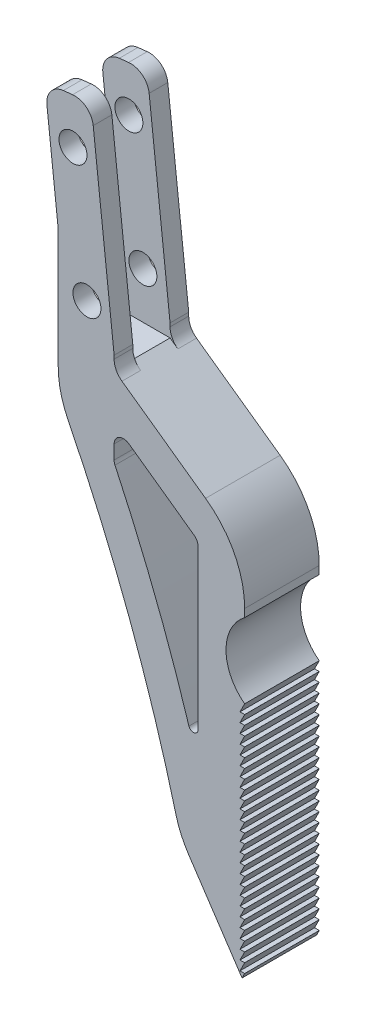
SolidWorks part; units mm, degrees
ref_plane "Front Plane" through (0, 0, 0) normal (0, 0, 1) x (1, 0, 0)
ref_plane "Top Plane" through (0, 0, 0) normal (0, 1, 0) x (1, 0, 0)
ref_plane "Right Plane" through (0, 0, 0) normal (1, 0, 0) x (0, 0, -1)
sketch "Sketch1" plane through (0, 0, 0) normal (0, 0, 1) x (1, 0, 0)
  line L0 (0, 0) -> (-20, 30.0054)
  line L1 (-20, 30.0054) -> (-20, 60.1354)
  line L2 (-20, 60.1354) -> (-21.4356, 73.0559)
  line L3 (-21.4356, 73.0559) -> (-16.4661, 73.608)
  line L4 (-16.4661, 73.608) -> (-14.0003, 51.4146)
  line L5 (-14.0003, 51.4146) -> (-14.0003, 50.0146)
  line L6 (-14.0003, 50.0146) -> (0, 40.0283)
  line L7 (0, 40.0283) -> (0, 0)
  dimension "D1" = 20
  dimension "D2" = 36.06
  dimension "D3" = 30.13
  dimension "D4" = 13
  dimension "D5" = 186.34
  dimension "D6" = 5
  dimension "D7" = 22.33
  dimension "D8" = 90
  dimension "D9" = 1.4
  dimension "D10" = 173.66
  dimension "D11" = 125.5
extrude "Boss-Extrude1" add sketch "Sketch1" along normal mid plane 8
sketch "Sketch3" plane through (0, 0, 0) normal (0, 0, 1) x (1, 0, 0)
  line L1 (-14.0003, 50.0146) -> (-34.0003, 50.0146)
  line L2 (-14.0003, 50.0146) -> (-14.0003, 75.0146)
  line L3 (-14.0003, 75.0146) -> (-34.0003, 75.0146)
  line L4 (-34.0003, 50.0146) -> (-34.0003, 75.0146)
  dimension "D1" = 20
  dimension "D2" = 25
extrude "Cut-Extrude1" cut sketch "Sketch3" against normal mid plane 4
sketch "Sketch5" plane through (0, 0, 4) normal (0, 0, 1) x (1, 0, 0)
  line L0 (0, 0) -> (0, 40.0283) construction
  arc A0 (0, 34.0283) -> (0, 26.0283) centre (3, 30.0283) ccw
  dimension "D1" = 5
  dimension "D2" = 6
  dimension "D3" = 10
extrude "Cut-Extrude2" cut sketch "Sketch5" against normal through all and the other way through all
sketch "Sketch6" plane through (0, 0, 4) normal (0, 0, 1) x (1, 0, 0)
  line L0 (0, 26.0283) -> (-0.5, 25.0283)
  line L1 (-0.5, 25.0283) -> (0, 25.0283)
  line L2 (0, 0) -> (0, 26.0283) construction
  line L3 (0, 25.0283) -> (0, 26.0283)
  dimension "D1" = 1
  dimension "D2" = 0.5
extrude "Cut-Extrude3" cut sketch "Sketch6" against normal through all
pattern_linear "LPattern1" count 26 spacing 1.0025 along (0, -1, 0) of "Cut-Extrude3"
sketch "Sketch7" plane through (0, 0, 4) normal (0, 0, 1) x (1, 0, 0)
  line L0 (-20, 60.1354) -> (-20, 30.0054) construction
  line L1 (-20, 30.0054) -> (-0.2759, 0.414) construction
  line L2 (-20, 45.0054) -> (-20, 30.0054)
  line L3 (-20, 30.0054) -> (-6.9551, 10.4345)
  arc A0 (-20, 45.0054) -> (-6.9551, 10.4345) centre (-162.1735, -28.3887) cw
  dimension "D3" = 160
  dimension "D1" = 15
  dimension "D2" = 23.52
extrude "Cut-Extrude4" cut sketch "Sketch7" against normal through all
sketch "Sketch8" plane through (0, 0, 4) normal (0, 0, 1) x (1, 0, 0)
  line L0 (-14.0041, 45.104) -> (-5, 38.6814)
  line L1 (-5, 38.6814) -> (-5, 17.744)
  line L2 (0, 34.0283) -> (0, 40.0283) construction
  line L3 (0, 40.0283) -> (-14.0003, 50.0146) construction
  line L4 (-14.0041, 45.104) -> (-14.0041, 41.444)
  arc A0 (-14.0041, 41.444) -> (-5, 17.744) centre (-158.6012, -27.0518) cw
  dimension "D6" = 160
  dimension "D1" = 4
  dimension "D2" = 5
  dimension "D3" = 3.66
  dimension "D4" = 23.7
  dimension "D5" = 11.06
extrude "Cut-Extrude5" cut sketch "Sketch8" against normal through all
fillet "Fillet1" radius 10 3 edges at (-20, 45.0054, 0) (-6.9551, 10.4345, 0) (0, 40.0283, 0)
fillet "Fillet2" radius 2 6 edges at (-14.0003, 50.0146, -3) (-14.0003, 50.0146, 3) (-16.4661, 73.608, -3) (-16.4661, 73.608, 3) (-21.4356, 73.0559, -3) (-21.4356, 73.0559, 3)
fillet "Fillet3" radius 1 3 edges at (-5, 38.6814, 0) (-14.0041, 41.444, 0) (-14.0041, 45.104, 0)
fillet "Fillet4" radius 0.5 1 edges at (-5, 17.744, 0)
sketch "Sketch9" plane through (0, 0, 4) normal (0, 0, 1) x (1, 0, 0)
  line L0 (-18.9509, 73.332) -> (-16.9157, 55.0147) construction
  line L1 (-18.4539, 73.3872) -> (-19.4478, 73.2767) construction
  line L2 (-14.0003, 51.4146) -> (-16.2453, 71.6203) construction
  circle A0 centre (-18.4164, 68.5216) radius 1.5
  circle A1 centre (-16.9157, 55.0147) radius 1.5
  dimension "D1" = 3
  dimension "D2" = 3
  dimension "D3" = 4.84
  dimension "D4" = 18.43
extrude "Cut-Extrude6" cut sketch "Sketch9" against normal through all
